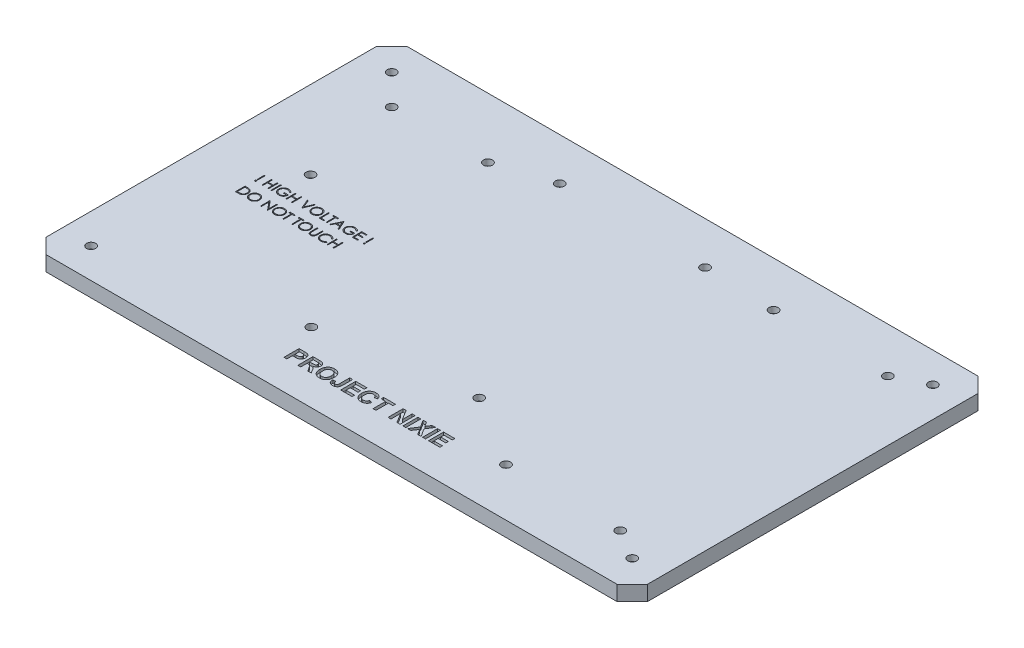
SolidWorks part; units mm, degrees
ref_plane "Front Plane" through (0, 0, 0) normal (0, 0, 1) x (1, 0, 0)
ref_plane "Top Plane" through (0, 0, 0) normal (0, 1, 0) x (1, 0, 0)
ref_plane "Right Plane" through (0, 0, 0) normal (1, 0, 0) x (0, 0, -1)
sketch "Sketch1" plane through (0, 0, 0) normal (0, 1, 0) x (1, 0, 0)
  line L1 (-111.1824, -29.2905) -> (88.8176, -29.2905)
  line L2 (-111.1824, -29.2905) -> (-111.1824, 90.7095)
  line L3 (-111.1824, 90.7095) -> (88.8176, 90.7095)
  line L4 (88.8176, -29.2905) -> (88.8176, 90.7095)
  dimension "D1" = 120
  dimension "D2" = 200
extrude "Boss-Extrude1" add sketch "Sketch1" along normal blind 5
sketch "Sketch2" plane through (0, 5, 0) normal (0, 1, 0) x (1, 0, 0)
  line L0 (88.8176, 90.7095) -> (-111.1824, 90.7095) construction
  line L1 (-111.1824, 90.7095) -> (-111.1824, -29.2905) construction
  circle A0 centre (-41.1824, 76.5895) radius 1.5
  circle A1 centre (7.1576, 76.5895) radius 1.5
  circle A2 centre (7.1576, 1.4595) radius 1.5
  circle A3 centre (-41.1824, -6.0405) radius 1.5
  point P12 (0, 0)
  point P13 (0, 0)
  point P14 (0, 0)
  dimension "D3" = 48.34
  dimension "D4" = 3
  dimension "D5" = 3
  dimension "D7" = 3
  dimension "D9" = 3
  dimension "D10" = 82.63
  dimension "D1" = 14.12
  dimension "D6" = 70
  dimension "D8" = 75.13
chamfer "Chamfer1" distance 5 angle 45 4 edges at (88.8176, 2.5, 29.2905) (88.8176, 2.5, -90.7095) (-111.1824, 2.5, -90.7095) (-111.1824, 2.5, 29.2905)
sketch "Sketch7" plane through (0, 5, 0) normal (0, 1, 0) x (1, 0, 0)
  line L0 (83.8176, 90.7095) -> (-106.1824, 90.7095) construction
  line L1 (-111.1824, 85.7095) -> (-111.1824, -24.2905) construction
  circle A0 centre (-59.1824, 70.7095) radius 1.5
  circle A1 centre (-91.1824, 70.7095) radius 1.5
  circle A2 centre (-85.1824, 37.7095) radius 1.5
  point P6 (0, 0)
  point P7 (0, 0)
  point P8 (0, 0)
  dimension "D1" = 3
  dimension "D2" = 3
  dimension "D3" = 3
  dimension "D4" = 32
  dimension "D5" = 6
  dimension "D6" = 33
  dimension "D7" = 20
  dimension "D8" = 20
extrude "Cut-Extrude7" cut sketch "Sketch2" against normal through all
sketch "Sketch10" plane through (0, 0, 0) normal (0, -1, 0) x (1, 0, 0)
  circle A0 centre (-41.1824, 6.0405) radius 3.075
  circle A1 centre (7.1576, -1.4595) radius 3.075
  circle A2 centre (-41.1824, -76.5895) radius 3.075
  circle A3 centre (7.1576, -76.5895) radius 3.075
  dimension "D1" = 6.15
  dimension "D2" = 6.15
  dimension "D3" = 6.15
  dimension "D4" = 6.15
extrude "Cut-Extrude8" cut sketch "Sketch10" against normal blind 3
sketch "Sketch11" plane through (0, 5, 0) normal (0, 1, 0) x (1, 0, 0)
  line L0 (83.8176, 90.7095) -> (-106.1824, 90.7095) construction
  line L1 (88.8176, -24.2905) -> (88.8176, 85.7095) construction
  line L2 (-106.1824, -29.2905) -> (83.8176, -29.2905) construction
  circle A0 centre (30.8176, 75.7095) radius 1.5
  circle A1 centre (68.8176, 75.7095) radius 1.5
  circle A2 centre (30.8176, -13.2905) radius 1.5
  circle A3 centre (68.8176, -13.2905) radius 1.5
  point P12 (0, 0)
  point P13 (0, 0)
  point P16 (0, 0)
  point P17 (0, 0)
  dimension "D1" = 3
  dimension "D2" = 3
  dimension "D3" = 3
  dimension "D4" = 3
  dimension "D5" = 38
  dimension "D6" = 89
  dimension "D7" = 15
  dimension "D8" = 20
  dimension "D9" = 38
  dimension "D12" = 16
extrude "Cut-Extrude9" cut sketch "Sketch11" against normal through all
sketch "Sketch12" plane through (0, 0, 0) normal (0, -1, 0) x (1, 0, 0)
  circle A0 centre (30.8176, 13.2905) radius 3.075
  circle A1 centre (68.8176, 13.2905) radius 3.075
  circle A2 centre (30.8176, -75.7095) radius 3.075
  circle A3 centre (68.8176, -75.7095) radius 3.075
  dimension "D1" = 6.15
  dimension "D2" = 6.15
  dimension "D3" = 6.15
  dimension "D4" = 6.15
extrude "Cut-Extrude10" cut sketch "Sketch12" against normal blind 3
extrude "Cut-Extrude11" cut sketch "Sketch7" against normal through all
sketch "Sketch13" plane through (0, 0, 0) normal (0, -1, 0) x (1, 0, 0)
  circle A0 centre (-85.1824, -37.7095) radius 3.075
  circle A1 centre (-91.1824, -70.7095) radius 3.075
  circle A2 centre (-59.1824, -70.7095) radius 3.075
  dimension "D1" = 6.15
  dimension "D2" = 6.15
  dimension "D3" = 6.15
extrude "Cut-Extrude12" cut sketch "Sketch13" against normal blind 3
sketch "Sketch14" plane through (0, 0, 0) normal (0, -1, 0) x (1, 0, 0)
  line L0 (-106.1824, 29.2905) -> (83.8176, 29.2905) construction
  line L1 (-111.1824, -85.7095) -> (-111.1824, 24.2905) construction
  line L2 (83.8176, -90.7095) -> (-106.1824, -90.7095) construction
  line L3 (88.8176, 24.2905) -> (88.8176, -85.7095) construction
  circle A0 centre (-101.1824, 19.2905) radius 1.5
  circle A1 centre (-101.1824, -80.7095) radius 1.5
  circle A2 centre (78.8176, 19.2905) radius 1.5
  circle A3 centre (78.8176, -80.7095) radius 1.5
  point P8 (0, 0)
  point P17 (0, 0)
  dimension "D1" = 3
  dimension "D4" = 3
  dimension "D5" = 3
  dimension "D8" = 3
  dimension "D2" = 10
  dimension "D3" = 10
  dimension "D6" = 10
  dimension "D7" = 10
extrude "Cut-Extrude13" cut sketch "Sketch14" against normal through all
sketch "Sketch16" plane through (0, 0, 0) normal (0, -1, 0) x (1, 0, 0)
  circle A0 centre (-101.1824, 19.2905) radius 3
  circle A1 centre (78.8176, 19.2905) radius 3
  circle A2 centre (-101.1824, -80.7095) radius 3
  circle A3 centre (78.8176, -80.7095) radius 3
  dimension "D1" = 6
  dimension "D2" = 6
  dimension "D3" = 6
  dimension "D4" = 6
extrude "Cut-Extrude14" cut sketch "Sketch16" against normal blind 3
sketch "Sketch17" plane through (0, 5, 0) normal (0, 1, 0) x (1, 0, 0)
  line L0 (-106.1824, -29.2905) -> (83.8176, -29.2905) construction
  line L1 (-11.1824, -29.2905) -> (-11.1824, 90.7095) construction
  line L2 (83.8176, 90.7095) -> (-106.1824, 90.7095) construction
  line L3 (-111.1824, -19.2905) -> (88.8176, -19.2905) construction
  line L4 (-111.1824, 85.7095) -> (-111.1824, -24.2905) construction
  line L5 (88.8176, -24.2905) -> (88.8176, 85.7095) construction
  text T0 "PROJECT NIXIE" font "Arial" height 5
  dimension "D1" = 10
sketch "Sketch20" plane through (0, 5, 0) normal (0, 1, 0) x (1, 0, 0)
  line L0 (-111.1824, -12.1931) -> (88.8176, -12.1931) construction
  line L1 (-111.1824, 85.7095) -> (-111.1824, -24.2905) construction
  line L2 (88.8176, -24.2905) -> (88.8176, 85.7095) construction
extrude "Cut-Extrude15" cut sketch "Sketch17" against normal blind 1
sketch "Sketch21" plane through (0, 5, 0) normal (0, 1, 0) x (1, 0, 0)
  line L0 (-11.1824, -29.2905) -> (-11.1824, 90.7095) construction
  line L1 (-106.1824, -29.2905) -> (83.8176, -29.2905) construction
  line L2 (83.8176, 90.7095) -> (-106.1824, 90.7095) construction
  line L3 (-111.1824, 85.7095) -> (-111.1824, -24.2905) construction
  line L4 (-61.1824, 30.7095) -> (-111.1824, 30.7095) construction
  line L6 (-61.1824, 30.7095) -> (-61.1824, 90.7095) construction
  text T0 "! HIGH VOLTAGE !\r\nDO NOT TOUCH"
extrude "Cut-Extrude16" cut sketch "Sketch21" against normal blind 1
